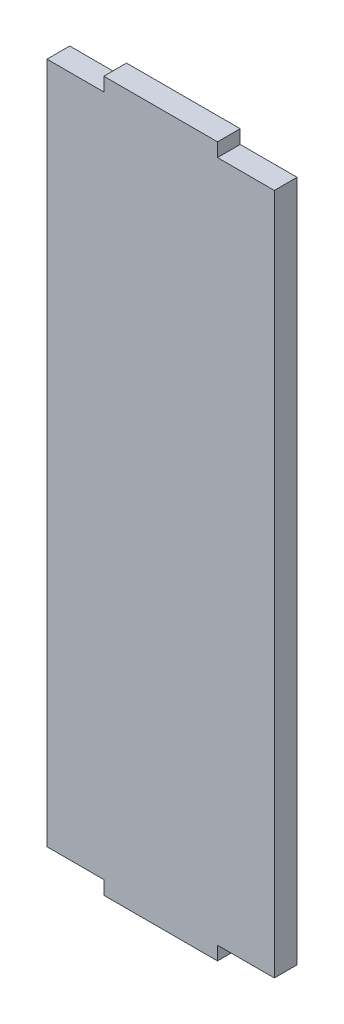
SolidWorks part; units mm, degrees
ref_plane "Front Plane" through (0, 0, 0) normal (0, 0, 1) x (1, 0, 0)
ref_plane "Top Plane" through (0, 0, 0) normal (0, 1, 0) x (1, 0, 0)
ref_plane "Right Plane" through (0, 0, 0) normal (1, 0, 0) x (0, 0, -1)
sketch "Sketch1" plane through (0, 0, 0) normal (0, 0, 1) x (1, 0, 0)
  line L1 (-25, 75) -> (25, 75)
  line L2 (-25, 75) -> (-25, -75)
  line L3 (-25, -75) -> (25, -75)
  line L4 (25, 75) -> (25, -75)
  line L5 (-25, 75) -> (25, -75) construction
  line L6 (-25, -75) -> (25, 75) construction
  point P0 (0, 0)
  dimension "D1" = 150
  dimension "D2" = 50
extrude "Boss-Extrude1" add sketch "Sketch1" along normal blind 5
sketch "Sketch2" plane through (0, 75, 0) normal (0, 1, 0) x (1, 0, 0)
  line L0 (25, -5) -> (-25, -5) construction
  line L1 (-12.5, 0) -> (12.5, 0)
  line L2 (-12.5, 0) -> (-12.5, -5)
  line L3 (-12.5, -5) -> (12.5, -5)
  line L4 (12.5, 0) -> (12.5, -5)
  line L5 (-12.5, 0) -> (12.5, -5) construction
  line L6 (-12.5, -5) -> (12.5, 0) construction
  line L7 (0, 0) -> (0, -50000) construction
  point P0 (0, -2.5)
  dimension "D1" = 25
extrude "Boss-Extrude2" add sketch "Sketch2" along normal blind 3
mirror "Mirror1" about plane through (0, 0, 0) normal (0, 1, 0) of "Boss-Extrude2"
